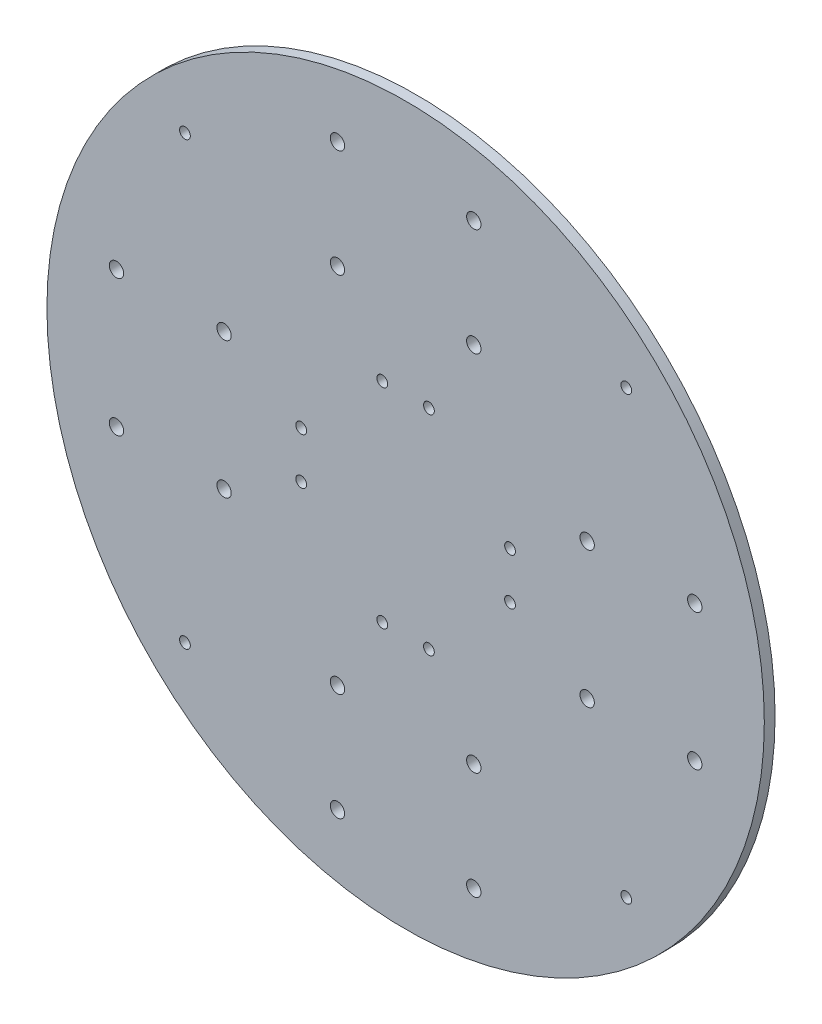
SolidWorks part; units mm, degrees
ref_plane "Alzado" through (0, 0, 0) normal (0, 0, 1) x (1, 0, 0)
ref_plane "Planta" through (0, 0, 0) normal (0, 1, 0) x (1, 0, 0)
ref_plane "Vista lateral" through (0, 0, 0) normal (1, 0, 0) x (0, 0, -1)
sketch "Croquis1" plane through (0, 0, 0) normal (0, 0, 1) x (1, 0, 0)
  line L0 (0, -100) -> (0, 100) construction
  line L1 (-100, 0) -> (100, 0) construction
  line L2 (-19, 80.6103) -> (19, 80.6103) construction
  line L3 (50.6103, 19) -> (80.6103, 19) construction
  line L4 (-23.5, 94.1103) -> (23.5, 94.1103) construction
  line L5 (-23.5, 94.1103) -> (-23.5, 37.1103) construction
  line L6 (-23.5, 37.1103) -> (23.5, 37.1103) construction
  line L7 (23.5, 94.1103) -> (23.5, 37.1103) construction
  circle A0 centre (0, 0) radius 100
  circle A1 centre (-19, 80.6103) radius 2
  circle A2 centre (19, 80.6103) radius 2
  circle A3 centre (-19, 50.6103) radius 2
  circle A4 centre (19, 50.6103) radius 2
  circle A5 centre (80.6103, 19) radius 2
  circle A6 centre (80.6103, -19) radius 2
  circle A7 centre (50.6103, 19) radius 2
  circle A8 centre (50.6103, -19) radius 2
  circle A9 centre (19, -80.6103) radius 2
  circle A10 centre (-19, -80.6103) radius 2
  circle A11 centre (19, -50.6103) radius 2
  circle A12 centre (-19, -50.6103) radius 2
  circle A13 centre (-80.6103, -19) radius 2
  circle A14 centre (-80.6103, 19) radius 2
  circle A15 centre (-50.6103, -19) radius 2
  circle A16 centre (-50.6103, 19) radius 2
  point P15 (0, 37.1103)
  point P20 (0, 80.6103)
  point P48 (0, 0)
  dimension "D1" = 200
  dimension "D2" = 4
  dimension "D3" = 34
  dimension "D4" = 26
  dimension "D6" = 3
  dimension "D5" = 11.5
  dimension "D7" = 57
  dimension "D8" = 47
  dimension "D10" = 19
  dimension "D11" = 50.6103
  dimension "D9" = 4
extrude "Saliente-Extruir1" add sketch "Croquis1" along normal blind 3 contours A0 A16 A15 A14 A13 A12 A11 A10 A9 A8 A7 A6 A5 A4 A3 A2 A1
sketch "Croquis2" plane through (0, 0, 3) normal (0, 0, 1) x (1, 0, 0)
  line L0 (6.5, 29.1103) -> (-6.5, 29.1103) construction
  circle A0 centre (19, 80.6103) radius 2 construction
  circle A1 centre (19, 50.6103) radius 2 construction
  circle A2 centre (-19, 50.6103) radius 2 construction
  circle A3 centre (-19, 80.6103) radius 2 construction
  circle A4 centre (19, 80.6103) radius 2
  circle A5 centre (19, 50.6103) radius 2
  circle A6 centre (-19, 50.6103) radius 2
  circle A7 centre (-19, 80.6103) radius 2
  circle A8 centre (-6.5, 29.1103) radius 1.5
  circle A9 centre (6.5, 29.1103) radius 1.5
  circle A10 centre (29.1103, 6.5) radius 1.5
  circle A11 centre (29.1103, -6.5) radius 1.5
  circle A12 centre (6.5, -29.1103) radius 1.5
  circle A13 centre (-6.5, -29.1103) radius 1.5
  circle A14 centre (-29.1103, -6.5) radius 1.5
  circle A15 centre (-29.1103, 6.5) radius 1.5
  point P16 (0, 29.1103)
  point P33 (0, 0)
  dimension "D1" = 3
  dimension "D2" = 3
  dimension "D3" = 18
  dimension "D4" = 13
  dimension "D5" = 4
extrude "Cortar-Extruir2" cut sketch "Croquis2" against normal up to surface (3 mm away) up to face at (-48.6103, 19, 0)
sketch "Croquis4" plane through (0, 0, 3) normal (0, 0, 1) x (1, 0, 0)
  line L0 (-61.5183, 61.5183) -> (0, 0) construction
  line L1 (0, 0) -> (-142.0416, 0) construction
  line L2 (61.5183, -61.5183) -> (0, 0) construction
  circle A0 centre (-61.5183, 61.5183) radius 1.5
  circle A1 centre (61.5183, 61.5183) radius 1.5
  circle A2 centre (0, 0) radius 100 construction
  circle A3 centre (61.5183, -61.5183) radius 1.5
  circle A4 centre (-61.5183, -61.5183) radius 1.5
  point P16 (0, 0)
  dimension "D2" = 3
  dimension "D1" = 45
  dimension "D3" = 13
  dimension "D5" = 13
  dimension "D4" = 4
extrude "Cortar-Extruir3" cut sketch "Croquis4" against normal up to surface (3 mm away) up to face at (8, -29.1103, 0)
